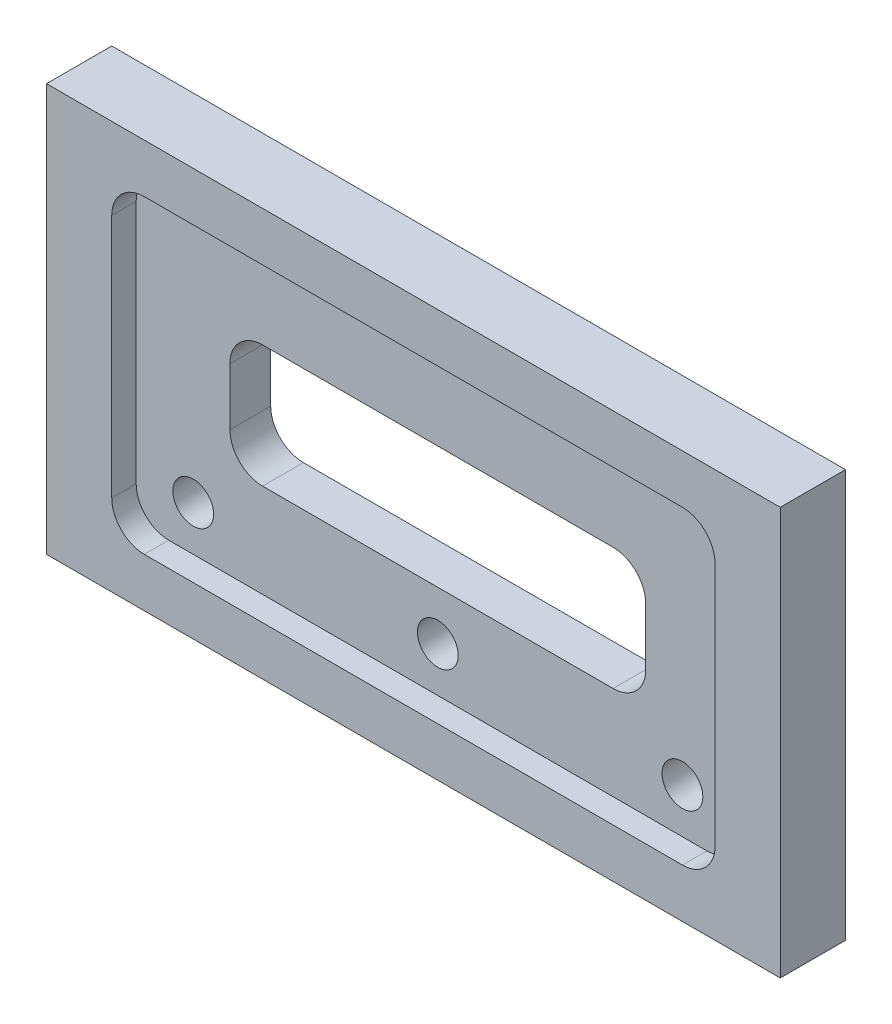
SolidWorks part; units mm, degrees
material "Mahogany"
ref_plane "Front Plane" through (0, 0, 0) normal (0, 0, 1) x (1, 0, 0)
ref_plane "Top Plane" through (0, 0, 0) normal (0, 1, 0) x (1, 0, 0)
ref_plane "Right Plane" through (0, 0, 0) normal (1, 0, 0) x (0, 0, -1)
sketch "Sketch1" plane through (0, 0, 0) normal (0, 0, 1) x (1, 0, 0)
  line L1 (-22.5, -12.5) -> (22.5, -12.5)
  line L2 (-22.5, -12.5) -> (-22.5, 12.5)
  line L3 (-22.5, 12.5) -> (22.5, 12.5)
  line L4 (22.5, -12.5) -> (22.5, 12.5)
  line L5 (-22.5, -12.5) -> (22.5, 12.5) construction
  line L6 (-22.5, 12.5) -> (22.5, -12.5) construction
  point P0 (0, 0)
  dimension "D1" = 25
  dimension "D2" = 45
extrude "Boss-Extrude1" add sketch "Sketch1" along normal blind 4
sketch "Sketch2" plane through (0, 0, 4) normal (0, 0, 1) x (1, 0, 0)
  line L1 (-18.5, -9.5) -> (18.5, -9.5)
  line L2 (-18.5, -9.5) -> (-18.5, 9.5)
  line L3 (-18.5, 9.5) -> (18.5, 9.5)
  line L4 (18.5, -9.5) -> (18.5, 9.5)
  line L5 (-18.5, -9.5) -> (18.5, 9.5) construction
  line L6 (-18.5, 9.5) -> (18.5, -9.5) construction
  point P0 (0, 0)
  dimension "D1" = 37
  dimension "D2" = 19
extrude "Cut-Extrude1" cut sketch "Sketch2" against normal blind 1.5
fillet "Fillet1" radius 2 4 edges at (-18.5, 9.5, 3.25) (18.5, 9.5, 3.25) (18.5, -9.5, 3.25) (-18.5, -9.5, 3.25)
sketch "Sketch3" plane through (0, 0, 2.5) normal (0, 0, 1) x (1, 0, 0)
  line L1 (-10.75, -3.75) -> (10.75, -3.75)
  line L2 (-12.75, -1.75) -> (-12.75, 1.75)
  line L3 (-10.75, 3.75) -> (10.75, 3.75)
  line L4 (12.75, -1.75) -> (12.75, 1.75)
  line L5 (-12.75, -3.75) -> (12.75, 3.75) construction
  line L6 (-12.75, 3.75) -> (12.75, -3.75) construction
  arc A0 (10.75, 3.75) -> (12.75, 1.75) centre (10.75, 1.75) cw
  arc A1 (10.75, -3.75) -> (12.75, -1.75) centre (10.75, -1.75) ccw
  arc A2 (-10.75, -3.75) -> (-12.75, -1.75) centre (-10.75, -1.75) cw
  arc A3 (-12.75, 1.75) -> (-10.75, 3.75) centre (-10.75, 1.75) cw
  point P0 (0, 0)
  dimension "D3" = 2
  dimension "D1" = 7.5
  dimension "D2" = 25.5
extrude "Cut-Extrude2" cut sketch "Sketch3" against normal through all
hole_wizard "Ø2.5mm Dowel Hole1" positions "Sketch4" profile "Sketch5" hole size "Ø2.5" standard "ANSI Metric" end condition through all
sketch "Sketch4" plane through (0, 0, 2.5) normal (0, 0, 1) x (1, 0, 0)
  line L0 (-10.75, -3.75) -> (10.75, -3.75) construction
  point P0 (-15, -6.75)
  point P2 (0, -6.75)
  point P4 (15, -6.75)
  point P9 (0, 0)
  dimension "D1" = 3
  dimension "D2" = 3
  dimension "D3" = 3
  dimension "D4" = 15
  dimension "D5" = 15
sketch "Sketch5" plane through (-15, -6.75, 2.5) normal (1, 0, 0) x (0, -1, 0)
  line L0 (0, 0) -> (0, 2.5)
  line L1 (0, 2.5) -> (1.25, 2.5)
  line L2 (1.25, 2.5) -> (1.25, 0)
  line L5 (1.25, 0) -> (0, 0)
  line L11 (0, -6.35) -> (0, 107.95) construction
  dimension "Thru Hole Dia." = 2.5
  dimension "Thru Hole Depth" = 2.5
